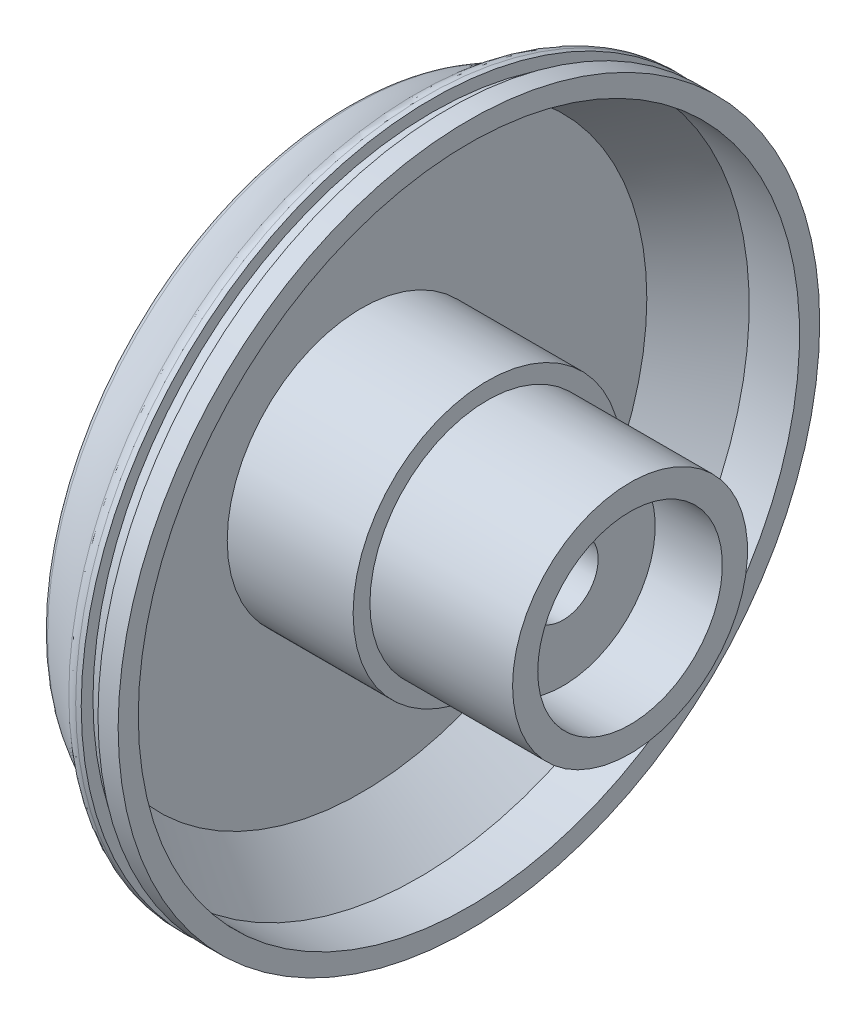
SolidWorks part; units mm, degrees
ref_plane "Front Plane" through (0, 0, 0) normal (0, 0, 1) x (1, 0, 0)
ref_plane "Top Plane" through (0, 0, 0) normal (0, 1, 0) x (1, 0, 0)
ref_plane "Right Plane" through (0, 0, 0) normal (1, 0, 0) x (0, 0, -1)
sketch "Sketch1" plane through (0, 0, 0) normal (0, 0, 1) x (1, 0, 0)
  line L0 (0, 222.3564) -> (0, 0) construction
  line L1 (0, 0) -> (266.9619, 0) construction
  line L2 (170, 55) -> (130, 55)
  line L3 (130, 55) -> (130, 21.01)
  line L4 (130, 21.01) -> (40, 21.01)
  line L5 (40, 21.01) -> (40, 55)
  line L6 (40, 55) -> (0, 55)
  line L7 (0, 55) -> (0, 180)
  line L8 (45, 209) -> (52, 209)
  line L9 (74, 209) -> (74, 197)
  line L10 (74, 197) -> (44, 197)
  line L11 (44, 197) -> (10, 170)
  line L12 (10, 170) -> (10, 80)
  line L13 (10, 80) -> (85, 80)
  line L14 (85, 80) -> (85, 70)
  line L15 (85, 70) -> (170, 70)
  line L16 (170, 70) -> (170, 55)
  line L17 (40, 55) -> (130, 55) construction
  line L18 (62, 209) -> (74, 209)
  line L20 (52, 209) -> (52, 202)
  line L21 (52, 202) -> (62, 202)
  line L22 (62, 209) -> (62, 202)
  arc A1 (0, 180) -> (45, 209) centre (-75.2366, 346.1602) ccw
  point P13 (170, 62.5)
  point P22 (40, 38.005)
  dimension "D1" = 209
  dimension "D21" = 182.4
  dimension "D2" = 170
  dimension "D3" = 21.01
  dimension "D4" = 70
  dimension "D5" = 80
  dimension "D6" = 40
  dimension "D7" = 40
  dimension "D8" = 45
  dimension "D9" = 55
  dimension "D10" = 55
  dimension "D11" = 10
  dimension "D12" = 29
  dimension "D13" = 30
  dimension "D14" = 45
  dimension "D15" = 12
  dimension "D16" = 180
  dimension "D17" = 90
  dimension "D18" = 7
  dimension "D19" = 10
  dimension "D20" = 7
revolve "Revolve1" add sketch "Sketch1" angle 360 about L1
fillet "Fillet1" radius 10 2 edges at (45, 0, 209) (0, 0, 180)
sketch "Sketch3" plane through (0, 0, 0) normal (-1, 0, 0) x (0, 0, 1)
  line L0 (0, 206.6487) -> (0, 0) construction
  line L1 (0, 0) -> (206.6487, 0) construction
  line L2 (0, 0) -> (146.1227, 146.1227) construction
  circle A0 centre (0, 0) radius 206.6487 construction
  arc A2 (56.8562, 105.6758) -> (98.0301, 69.2106) centre (0, 0) cw construction
  arc A7 (130.7068, 92.2808) -> (75.8083, 140.9011) centre (0, 0) ccw
  arc A8 (65.3534, 46.1404) -> (37.9041, 70.4505) centre (0, 0) ccw
  arc A9 (65.3534, 46.1404) -> (130.7068, 92.2808) centre (98.0301, 69.2106) ccw
  arc A10 (75.8083, 140.9011) -> (37.9041, 70.4505) centre (56.8562, 105.6758) ccw
  arc A11 (105.6758, -56.8562) -> (69.2106, -98.0301) centre (0, 0) cw construction
  arc A12 (92.2808, -130.7068) -> (140.9011, -75.8083) centre (0, 0) ccw
  arc A13 (46.1404, -65.3534) -> (70.4505, -37.9041) centre (0, 0) ccw
  arc A14 (46.1404, -65.3534) -> (92.2808, -130.7068) centre (69.2106, -98.0301) ccw
  arc A15 (140.9011, -75.8083) -> (70.4505, -37.9041) centre (105.6758, -56.8562) ccw
  arc A16 (-56.8562, -105.6758) -> (-98.0301, -69.2106) centre (0, 0) cw construction
  arc A17 (-130.7068, -92.2808) -> (-75.8083, -140.9011) centre (0, 0) ccw
  arc A18 (-65.3534, -46.1404) -> (-37.9041, -70.4505) centre (0, 0) ccw
  arc A19 (-65.3534, -46.1404) -> (-130.7068, -92.2808) centre (-98.0301, -69.2106) ccw
  arc A20 (-75.8083, -140.9011) -> (-37.9041, -70.4505) centre (-56.8562, -105.6758) ccw
  arc A21 (-105.6758, 56.8562) -> (-69.2106, 98.0301) centre (0, 0) cw construction
  arc A22 (-92.2808, 130.7068) -> (-140.9011, 75.8083) centre (0, 0) ccw
  arc A23 (-46.1404, 65.3534) -> (-70.4505, 37.9041) centre (0, 0) ccw
  arc A24 (-46.1404, 65.3534) -> (-92.2808, 130.7068) centre (-69.2106, 98.0301) ccw
  arc A25 (-140.9011, 75.8083) -> (-70.4505, 37.9041) centre (-105.6758, 56.8562) ccw
  point P11 (79.5605, 89.8339)
  point P21 (89.8339, -79.5605)
  point P28 (-79.5605, -89.8339)
  point P35 (-89.8339, 79.5605)
  point P40 (0, 0)
  dimension "D2" = 55
  dimension "D3" = 160
  dimension "D4" = 80
  dimension "D1" = 45
  dimension "D5" = 4
